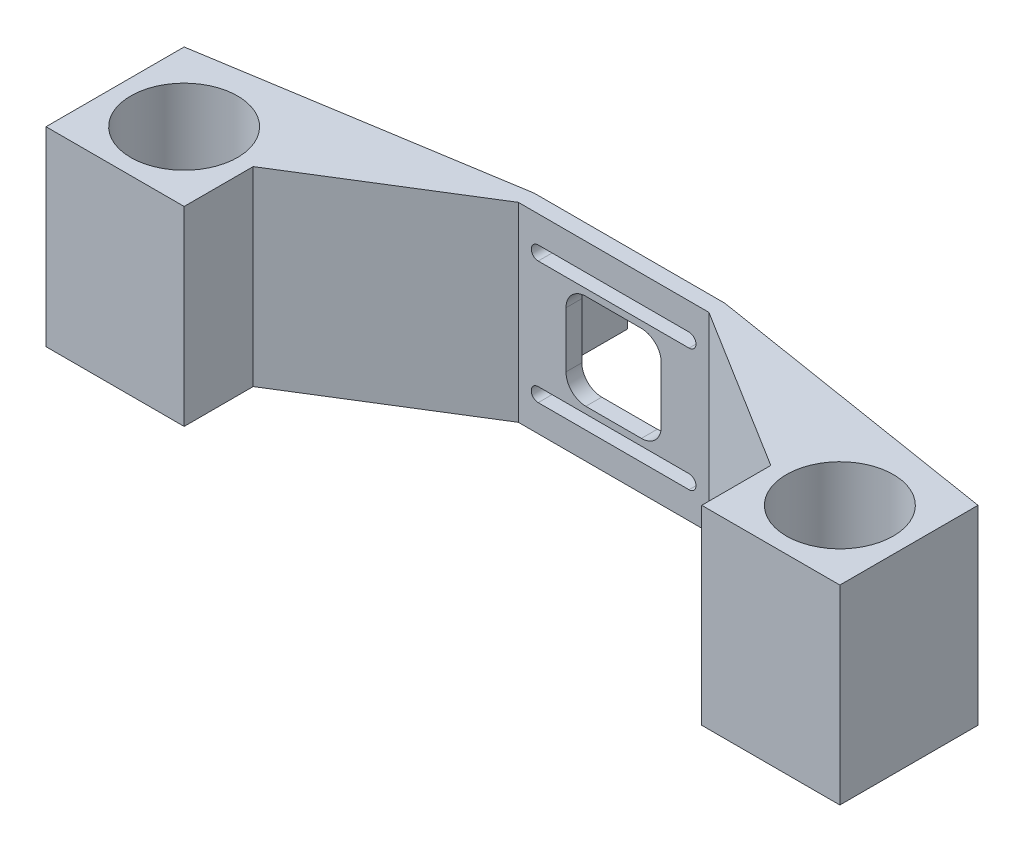
SolidWorks part; units mm, degrees
ref_plane "Front Plane" through (0, 0, 0) normal (0, 0, 1) x (1, 0, 0)
ref_plane "Top Plane" through (0, 0, 0) normal (0, 1, 0) x (1, 0, 0)
ref_plane "Right Plane" through (0, 0, 0) normal (1, 0, 0) x (0, 0, -1)
sketch "Sketch2" plane through (0, 0, 0) normal (0, 1, 0) x (1, 0, 0)
  line L0 (-17.4, -17.4) -> (82.6, -17.4) construction
  line L1 (-17.4, -17.4) -> (17.4, -17.4)
  line L2 (-17.4, -17.4) -> (-17.4, 17.4)
  line L5 (0, 17.4) -> (0, -17.4) construction
  line L6 (-17.4, 0) -> (17.4, 0) construction
  line L7 (82.6, -17.4) -> (82.6, 29.6) construction
  line L8 (17.4, -17.4) -> (17.4, 0)
  line L9 (82.6, 29.6) -> (58.6, 29.6)
  line L10 (82.6, 29.6) -> (82.6, 25.6)
  line L11 (82.6, 25.6) -> (58.6, 25.6)
  line L13 (17.4, 0) -> (58.6, 25.6)
  line L14 (58.6, 29.6) -> (-17.4, 17.4)
  circle A0 centre (0, 0) radius 13.45
  point P0 (0, 0)
  dimension "D3" = 26.9
  dimension "D8" = 17.4
  dimension "D9" = 17.4
  dimension "D1" = 34.8
  dimension "D2" = 34.8
  dimension "D4" = 100
  dimension "D5" = 47
  dimension "D6" = 24
  dimension "D7" = 4
extrude "Boss-Extrude1" add sketch "Sketch2" along normal blind 48
sketch3d "3DSketch1"
  line L0 (82.6, 0, -29.6) -> (82.6, 0, -25.6) construction
  line L1 (82.6, 0, -25.6) -> (82.6, 48, -25.6) construction
ref_plane "Plane1" through (82.6, 0, 0) normal (1, 0, 0) x (0, 0, -1)
mirror "Mirror1" about plane through (82.6, 0, 0) normal (1, 0, 0) of "Boss-Extrude1"
sketch "Sketch4" plane through (0, 0, -29.6) normal (0, 0, -1) x (-1, 0, 0)
  line L0 (-106.6, 24) -> (-58.6, 24) construction
  line L1 (-58.6, 48) -> (-58.6, 0) construction
  line L2 (-101.6, 8.55) -> (-63.6, 8.55) construction
  line L3 (-101.6, 10.3) -> (-63.6, 10.3)
  line L4 (-82.6, 0) -> (-82.6, 48) construction
  line L5 (-101.6, 6.8) -> (-63.6, 6.8)
  line L6 (-101.6, 39.45) -> (-63.6, 39.45) construction
  line L7 (-101.6, 37.7) -> (-63.6, 37.7)
  line L8 (-101.6, 41.2) -> (-63.6, 41.2)
  line L10 (-89.6, 12) -> (-75.6, 12)
  line L11 (-94.6, 17) -> (-94.6, 31)
  line L12 (-89.6, 36) -> (-75.6, 36)
  line L13 (-70.6, 17) -> (-70.6, 31)
  line L14 (-94.6, 12) -> (-70.6, 36) construction
  line L15 (-94.6, 36) -> (-70.6, 12) construction
  arc A0 (-101.6, 10.3) -> (-101.6, 6.8) centre (-101.6, 8.55) ccw
  arc A1 (-63.6, 6.8) -> (-63.6, 10.3) centre (-63.6, 8.55) ccw
  arc A2 (-101.6, 37.7) -> (-101.6, 41.2) centre (-101.6, 39.45) cw
  arc A3 (-63.6, 41.2) -> (-63.6, 37.7) centre (-63.6, 39.45) cw
  arc A5 (-94.6, 17) -> (-89.6, 12) centre (-89.6, 17) ccw
  arc A6 (-75.6, 12) -> (-70.6, 17) centre (-75.6, 17) ccw
  arc A7 (-70.6, 31) -> (-75.6, 36) centre (-75.6, 31) ccw
  arc A8 (-94.6, 31) -> (-89.6, 36) centre (-89.6, 31) cw
  point P5 (-82.6, 24)
  point P7 (-82.6, 8.55)
  point P10 (-82.6, 24)
  point P17 (-82.6, 39.45)
  dimension "D4" = 24
  dimension "D6" = 5
  dimension "D1" = 15.45
  dimension "D2" = 1.75
  dimension "D3" = 38
  dimension "D5" = 24
extrude "Cut-Extrude1" cut sketch "Sketch4" against normal blind 10
ref_plane "Plane2" through (0, 0, -29.6) normal (0, 0, -1) x (-1, 0, 0)
sketch "Sketch5" plane through (0, 0, -29.6) normal (0, 0, -1) x (-1, 0, 0)
  line L0 (-116.8963, 24.0999) -> (-31.0979, 24.0999) construction
  line L1 (-82.6, 2.2) -> (-82.6, -2.2) construction
  line L3 (-69.1, 31.0999) -> (-55.1, 31.0999)
  line L4 (-69.1, 31.0999) -> (-69.1, 17.0999)
  line L5 (-69.1, 17.0999) -> (-55.1, 17.0999)
  line L6 (-55.1, 31.0999) -> (-55.1, 17.0999)
  line L7 (-69.1, 31.0999) -> (-55.1, 17.0999) construction
  line L8 (-69.1, 17.0999) -> (-55.1, 31.0999) construction
  circle A0 centre (-62.1, 24.0999) radius 4.1
  dimension "D1" = 8.2
  dimension "D2" = 20.5
  dimension "D3" = 14
  dimension "D4" = 14
extrude "Boss-Extrude2" add sketch "Sketch5" along normal blind 13 and the other way blind 2
